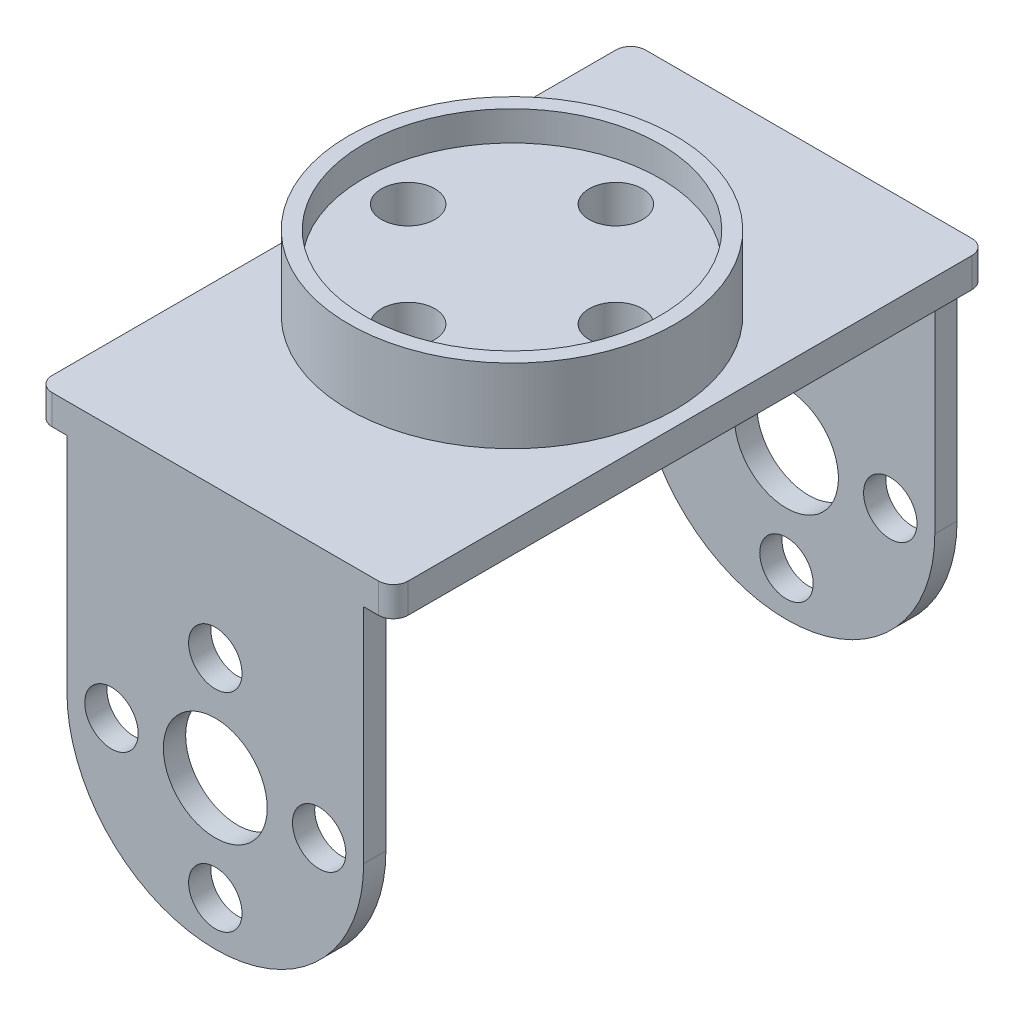
SolidWorks part; units mm, degrees
ref_plane "前视基准面" through (0, 0, 0) normal (0, 0, 1) x (1, 0, 0)
ref_plane "上视基准面" through (0, 0, 0) normal (0, 1, 0) x (1, 0, 0)
ref_plane "右视基准面" through (0, 0, 0) normal (1, 0, 0) x (0, 0, -1)
other "Configuration Table"
sketch "草图1" plane through (0, 0, 0) normal (0, 0, 1) x (1, 0, 0)
  line L1 (0, 0) -> (-24, 0)
  line L2 (0, 0) -> (0, 30)
  line L3 (0, 30) -> (-24, 30)
  line L4 (-24, 0) -> (-24, 30)
  dimension "D1" = 30
  dimension "D2" = 24
extrude "凸台-拉伸1" add sketch "草图1" along normal blind 40
sketch "草图2" plane through (0, 0, 0) normal (0, 0, -1) x (-1, 0, 0)
  line L0 (12, 0) -> (12, 50000) construction
  line L1 (24, 0) -> (0, 0) construction
  line L2 (0, 30) -> (24, 30) construction
  line L3 (2, 13) -> (2, 28)
  line L4 (2, 28) -> (0, 28)
  line L5 (0, 0) -> (0, 30) construction
  line L6 (24, 30) -> (24, 28)
  line L7 (22, 28) -> (24, 28)
  line L8 (22, 13) -> (22, 28)
  line L10 (0, 30) -> (0, 0)
  line L11 (0, 0) -> (24, 0)
  line L12 (24, 0) -> (24, 30)
  line L13 (24, 30) -> (0, 30)
  line L14 (0, 30) -> (0, 28)
  line L17 (24, 30) -> (0, 30)
  circle A0 centre (12, 13) radius 10
  point P4 (12, 0)
  line M13 (0, 30) -> (0, 0)
  line M14 (0, 0) -> (24, 0)
  line M15 (24, 0) -> (24, 30)
  dimension "D1" = 20
  dimension "D2" = 17
  dimension "D3" = 0
  dimension "D4" = 2
extrude "切除-拉伸1" cut sketch "草图2" against normal through all contours L0 A0 L3 L4 M14 M13 | L0 L7 L8 A0 M14 M15
ref_plane "基准面1" through (0, 0, 20) normal (0, 0, -1) x (-1, 0, 0)
sketch "草图3" plane through (0, 0, 20) normal (0, 0, -1) x (-1, 0, 0)
  line L0 (2, 28) -> (22, 28)
  line L7 (0, 30) -> (0, 28)
  line L8 (0, 28) -> (2, 28)
  line L9 (2, 28) -> (2, 13)
  line L10 (22, 13) -> (22, 28)
  line L11 (22, 28) -> (24, 28)
  line L12 (24, 28) -> (24, 30)
  line L13 (24, 30) -> (0, 30)
  line L14 (0, 30) -> (0, 28)
  line L15 (0, 28) -> (2, 28)
  line L16 (2, 28) -> (2, 13)
  line L17 (22, 13) -> (22, 28)
  line L18 (22, 28) -> (24, 28)
  line L19 (24, 28) -> (24, 30)
  line L20 (24, 30) -> (0, 30)
  arc A1 (2, 13) -> (22, 13) centre (12, 13) ccw
  arc A2 (2, 13) -> (22, 13) centre (12, 13) ccw
  dimension "D1" = 0
extrude "切除-拉伸2" cut sketch "草图3" against normal blind 18.5 and the other way blind 18.5 contours L16 A2 L17 L0
sketch "草图4" plane through (0, 0, 0) normal (0, 0, -1) x (-1, 0, 0)
  circle A0 centre (12, 13) radius 7 construction
  circle A1 centre (12, 6) radius 1.8
  circle A5 centre (12, 13) radius 3.5
  circle A6 centre (12, 20) radius 1.8
  circle A7 centre (19, 13) radius 1.8
  circle A8 centre (5, 13) radius 1.8
  point P14 (11.0448, 11.9373)
  dimension "D1" = 14
  dimension "D2" = 3.6
  dimension "D4" = 7
  dimension "D3" = 3.6
  dimension "D5" = 3.6
  dimension "D6" = 3.6
extrude "切除-拉伸3" cut sketch "草图4" against normal up to surface (40 mm away) up to face at (-12, 23.5, 40)
sketch "草图5" plane through (0, 30, 0) normal (0, 1, 0) x (1, 0, 0)
  line L0 (-24, -20) -> (49976, -20) construction
  line L1 (-24, -40) -> (-24, 0) construction
  line L2 (-12, 0) -> (-12, -50000) construction
  line L3 (0, 0) -> (-24, 0) construction
  circle A0 centre (-12, -20) radius 10
  circle A1 centre (-12, -20) radius 11
  point P4 (-24, -20)
  point P9 (-12, 0)
  dimension "D1" = 20
  dimension "D2" = 22
extrude "凸台-拉伸2" add sketch "草图5" along normal blind 5 separate body contours A1 A0
sketch "草图6" plane through (0, 35, 0) normal (0, 1, 0) x (1, 0, 0)
  circle A0 centre (-12, -20) radius 10
  dimension "D1" = 20
extrude "切除-拉伸4" cut sketch "草图6" against normal blind 2
sketch "草图7" plane through (0, 33, 0) normal (0, 1, 0) x (1, 0, 0)
  circle A0 centre (-12, -20) radius 7 construction
  circle A1 centre (-12, -13) radius 1.8
  circle A2 centre (-5, -20) radius 1.8
  circle A3 centre (-12, -27) radius 1.8
  circle A4 centre (-19, -20) radius 1.8
  point P14 (-12, -20)
  dimension "D1" = 14
  dimension "D2" = 3.6
  dimension "D3" = 4
extrude "切除-拉伸5" cut sketch "草图7" against normal through all
sketch "草图8" plane through (0, 28, 0) normal (0, -1, 0) x (1, 0, 0)
  circle A0 centre (-12, 27) radius 2.7
  circle A1 centre (-5, 20) radius 2.7
  circle A2 centre (-19, 20) radius 2.7
  circle A3 centre (-12, 13) radius 2.7
  dimension "D1" = 5.4
  dimension "D2" = 5.4
  dimension "D3" = 5.4
  dimension "D4" = 5.4
extrude "切除-拉伸6" cut sketch "草图8" against normal blind 2
fillet "圆角1" radius 1 4 edges at (-24, 29, 40) (0, 29, 40) (0, 29, 0) (-24, 29, 0)
